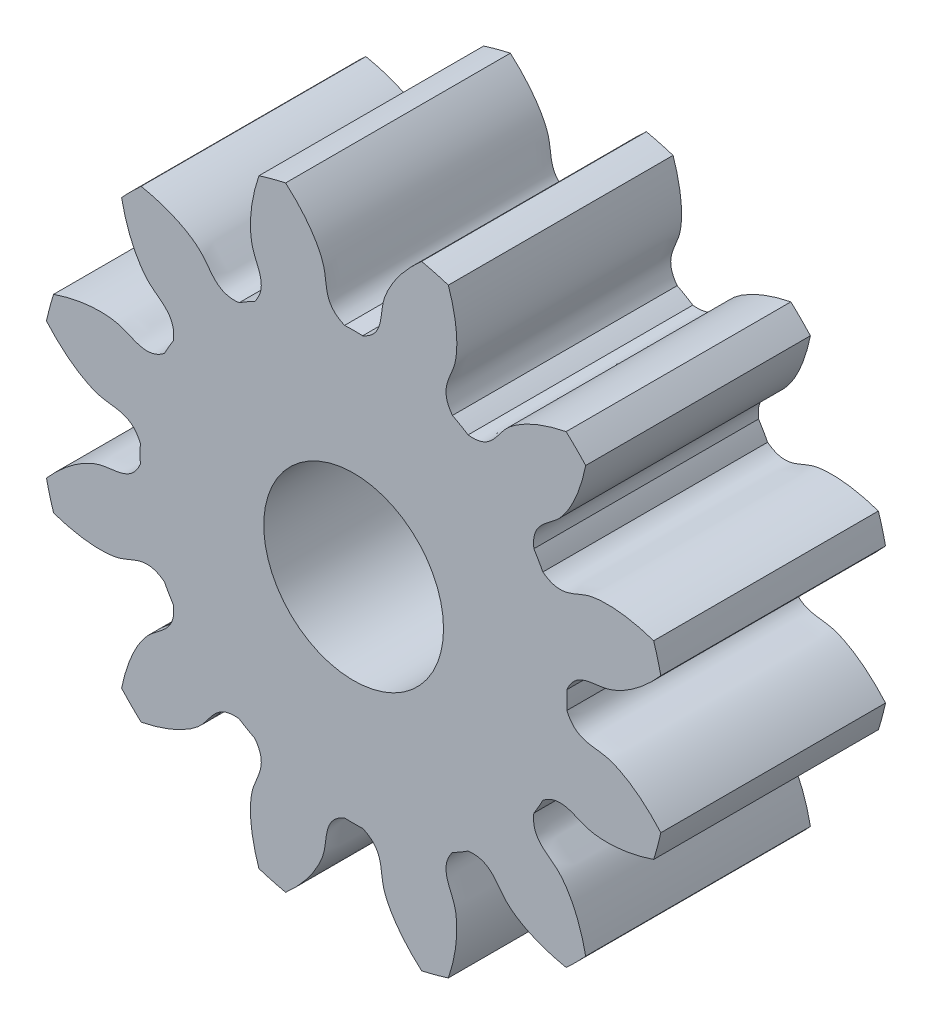
SolidWorks part; units mm, degrees
ref_plane "前视基准面" through (0, 0, 0) normal (0, 0, 1) x (1, 0, 0)
ref_plane "上视基准面" through (0, 0, 0) normal (0, 1, 0) x (1, 0, 0)
ref_plane "右视基准面" through (0, 0, 0) normal (1, 0, 0) x (0, 0, -1)
sketch "草图1" plane through (0, 0, 0) normal (0, 0, 1) x (1, 0, 0)
  arc A0 (2.4753, 14.2124) -> (1.8808, 14.0531) centre (3.988, 7.3778) ccw
  arc A1 (4.1888, 12.1235) -> (3.7871, 12.1235) centre (3.988, 7.3778) ccw
  arc A2 (6.0952, 14.0531) -> (5.5007, 14.2124) centre (3.988, 7.3778) ccw
  arc A3 (6.5348, 11.3873) -> (6.1869, 11.5881) centre (3.988, 7.3778) ccw
  arc A4 (9.1506, 12.1051) -> (8.7153, 12.5403) centre (3.988, 7.3778) ccw
  arc A5 (8.1983, 9.5767) -> (7.9975, 9.9246) centre (3.988, 7.3778) ccw
  arc A6 (10.8226, 8.8905) -> (10.6633, 9.485) centre (3.988, 7.3778) ccw
  arc A7 (8.7337, 7.1769) -> (8.7337, 7.5786) centre (3.988, 7.3778) ccw
  arc A8 (10.6633, 5.2705) -> (10.8226, 5.865) centre (3.988, 7.3778) ccw
  arc A9 (7.9975, 4.831) -> (8.1983, 5.1788) centre (3.988, 7.3778) ccw
  arc A10 (8.7153, 2.2152) -> (9.1506, 2.6504) centre (3.988, 7.3778) ccw
  arc A11 (6.1869, 3.1674) -> (6.5348, 3.3683) centre (3.988, 7.3778) ccw
  arc A12 (5.5007, 0.5432) -> (6.0952, 0.7025) centre (3.988, 7.3778) ccw
  arc A13 (3.7871, 2.632) -> (4.1888, 2.632) centre (3.988, 7.3778) ccw
  arc A14 (1.8808, 0.7025) -> (2.4753, 0.5432) centre (3.988, 7.3778) ccw
  arc A15 (1.4412, 3.3683) -> (1.789, 3.1674) centre (3.988, 7.3778) ccw
  arc A16 (-1.1746, 2.6504) -> (-0.7394, 2.2152) centre (3.988, 7.3778) ccw
  arc A17 (-0.2224, 5.1788) -> (-0.0215, 4.831) centre (3.988, 7.3778) ccw
  arc A18 (-2.8466, 5.865) -> (-2.6873, 5.2705) centre (3.988, 7.3778) ccw
  arc A19 (-0.7578, 7.5786) -> (-0.7578, 7.1769) centre (3.988, 7.3778) ccw
  arc A20 (-2.6873, 9.485) -> (-2.8466, 8.8905) centre (3.988, 7.3778) ccw
  arc A21 (-0.0215, 9.9246) -> (-0.2224, 9.5767) centre (3.988, 7.3778) ccw
  arc A22 (-0.7394, 12.5403) -> (-1.1746, 12.1051) centre (3.988, 7.3778) ccw
  arc A23 (1.789, 11.5881) -> (1.4412, 11.3873) centre (3.988, 7.3778) ccw
  circle A24 centre (3.988, 7.3778) radius 2
  spline S0 degree 3 poles (1.789, 11.5881) (2.1029, 12.0044) (1.813, 12.2937) (1.727, 12.6508) (1.7189, 12.6894) (1.71, 12.7428) (1.7021, 12.8055) (1.6959, 12.8774) (1.6921, 12.9585) (1.6916, 13.0487) (1.6949, 13.1479) (1.7029, 13.2559) (1.7162, 13.3724) (1.7391, 13.5207) (1.7769, 13.7033) (1.8272, 13.8894) (1.8652, 14.0073) (1.8808, 14.0531) knots 0 0 0 0 0.218015 0.222044 0.231522 0.242897 0.256167 0.271332 0.288394 0.307351 0.328204 0.350953 0.375597 0.402137 0.445502 0.493132 0.523596 0.523596 0.523596 0.523596
  spline S1 degree 3 poles (2.4753, 14.2124) (2.5311, 14.1635) (2.6222, 14.0794) (2.7418, 13.9578) (2.8358, 13.8543) (2.9197, 13.754) (2.9941, 13.6575) (3.0594, 13.5655) (3.116, 13.4786) (3.1645, 13.3972) (3.2054, 13.3219) (3.2393, 13.2531) (3.2668, 13.1912) (3.2884, 13.1367) (3.3028, 13.0959) (3.3118, 13.0673) (3.4136, 12.7226) (3.3072, 12.3271) (3.7871, 12.1235) knots 0.476404 0.476404 0.476404 0.476404 0.523219 0.554498 0.583882 0.61137 0.636962 0.660659 0.682459 0.702364 0.720374 0.736487 0.750705 0.763028 0.773454 0.777956 0.781985 1 1 1 1
  spline S2 degree 3 poles (4.1888, 12.1235) (4.6688, 12.3271) (4.5624, 12.7226) (4.6664, 13.0748) (4.6787, 13.1123) (4.6977, 13.163) (4.7222, 13.2213) (4.7528, 13.2866) (4.7901, 13.3588) (4.8347, 13.4372) (4.8872, 13.5214) (4.9481, 13.6109) (5.0179, 13.7052) (5.1118, 13.8221) (5.2359, 13.9614) (5.3725, 14.0974) (5.4643, 14.1806) (5.5007, 14.2124) knots 0 0 0 0 0.218015 0.222044 0.231522 0.242897 0.256167 0.271332 0.288394 0.307351 0.328204 0.350953 0.375597 0.402137 0.445502 0.493132 0.523596 0.523596 0.523596 0.523596
  spline S3 degree 3 poles (6.0952, 14.0531) (6.1192, 13.9828) (6.156, 13.8645) (6.1988, 13.6994) (6.2284, 13.5627) (6.251, 13.4338) (6.2672, 13.3131) (6.2777, 13.2008) (6.2833, 13.0972) (6.2846, 13.0025) (6.2823, 12.9168) (6.2773, 12.8403) (6.2701, 12.773) (6.2616, 12.7149) (6.2536, 12.6725) (6.2472, 12.6431) (6.163, 12.2937) (5.8731, 12.0044) (6.1869, 11.5881) knots 0.476404 0.476404 0.476404 0.476404 0.523219 0.554498 0.583882 0.61137 0.636962 0.660659 0.682459 0.702364 0.720374 0.736487 0.750705 0.763028 0.773454 0.777956 0.781985 1 1 1 1
  spline S4 degree 3 poles (6.5348, 11.3873) (7.0522, 11.3236) (7.1578, 11.7193) (7.424, 11.9724) (7.4535, 11.9987) (7.4952, 12.0331) (7.5455, 12.0713) (7.6047, 12.1126) (7.6731, 12.1564) (7.751, 12.202) (7.8385, 12.2487) (7.936, 12.2958) (8.0436, 12.3426) (8.1835, 12.3968) (8.3605, 12.4554) (8.5468, 12.5048) (8.6679, 12.531) (8.7153, 12.5403) knots 0 0 0 0 0.218015 0.222044 0.231522 0.242897 0.256167 0.271332 0.288394 0.307351 0.328204 0.350953 0.375597 0.402137 0.445502 0.493132 0.523596 0.523596 0.523596 0.523596
  spline S5 degree 3 poles (9.1506, 12.1051) (9.1362, 12.0323) (9.1089, 11.9114) (9.0634, 11.7471) (9.0207, 11.6139) (8.9758, 11.491) (8.9295, 11.3783) (8.8825, 11.2758) (8.8355, 11.1833) (8.7892, 11.1006) (8.7445, 11.0275) (8.7018, 10.9638) (8.662, 10.9091) (8.6256, 10.8631) (8.5974, 10.8303) (8.5771, 10.8081) (8.3295, 10.5476) (7.9338, 10.442) (7.9975, 9.9246) knots 0.476404 0.476404 0.476404 0.476404 0.523219 0.554498 0.583882 0.61137 0.636962 0.660659 0.682459 0.702364 0.720374 0.736487 0.750705 0.763028 0.773454 0.777956 0.781985 1 1 1 1
  spline S6 degree 3 poles (8.1983, 9.5767) (8.6146, 9.2628) (8.9039, 9.5528) (9.261, 9.6388) (9.2996, 9.6468) (9.353, 9.6558) (9.4157, 9.6637) (9.4876, 9.6699) (9.5687, 9.6736) (9.6589, 9.6742) (9.7581, 9.6709) (9.8661, 9.6629) (9.9827, 9.6496) (10.1309, 9.6267) (10.3135, 9.5888) (10.4996, 9.5385) (10.6175, 9.5006) (10.6633, 9.485) knots 0 0 0 0 0.218015 0.222044 0.231522 0.242897 0.256167 0.271332 0.288394 0.307351 0.328204 0.350953 0.375597 0.402137 0.445502 0.493132 0.523596 0.523596 0.523596 0.523596
  spline S7 degree 3 poles (10.8226, 8.8905) (10.7737, 8.8346) (10.6896, 8.7436) (10.5681, 8.624) (10.4645, 8.53) (10.3642, 8.446) (10.2677, 8.3716) (10.1758, 8.3063) (10.0888, 8.2497) (10.0074, 8.2012) (9.9321, 8.1603) (9.8633, 8.1264) (9.8014, 8.099) (9.7469, 8.0774) (9.7061, 8.063) (9.6775, 8.0539) (9.3328, 7.9521) (8.9373, 8.0586) (8.7337, 7.5786) knots 0.476404 0.476404 0.476404 0.476404 0.523219 0.554498 0.583882 0.61137 0.636962 0.660659 0.682459 0.702364 0.720374 0.736487 0.750705 0.763028 0.773454 0.777956 0.781985 1 1 1 1
  spline S8 degree 3 poles (8.7337, 7.1769) (8.9373, 6.697) (9.3328, 6.8034) (9.685, 6.6994) (9.7225, 6.687) (9.7732, 6.6681) (9.8315, 6.6436) (9.8968, 6.613) (9.969, 6.5757) (10.0474, 6.5311) (10.1316, 6.4786) (10.2212, 6.4177) (10.3154, 6.3479) (10.4324, 6.2539) (10.5716, 6.1298) (10.7076, 5.9932) (10.7908, 5.9014) (10.8226, 5.865) knots 0 0 0 0 0.218015 0.222044 0.231522 0.242897 0.256167 0.271332 0.288394 0.307351 0.328204 0.350953 0.375597 0.402137 0.445502 0.493132 0.523596 0.523596 0.523596 0.523596
  spline S9 degree 3 poles (10.6633, 5.2705) (10.593, 5.2466) (10.4747, 5.2097) (10.3096, 5.167) (10.1729, 5.1374) (10.0441, 5.1148) (9.9233, 5.0986) (9.811, 5.088) (9.7074, 5.0825) (9.6127, 5.0812) (9.527, 5.0834) (9.4505, 5.0885) (9.3832, 5.0956) (9.3252, 5.1042) (9.2827, 5.1121) (9.2533, 5.1186) (8.9039, 5.2028) (8.6146, 5.4927) (8.1983, 5.1788) knots 0.476404 0.476404 0.476404 0.476404 0.523219 0.554498 0.583882 0.61137 0.636962 0.660659 0.682459 0.702364 0.720374 0.736487 0.750705 0.763028 0.773454 0.777956 0.781985 1 1 1 1
  spline S10 degree 3 poles (7.9975, 4.831) (7.9338, 4.3135) (8.3295, 4.2079) (8.5826, 3.9417) (8.6089, 3.9123) (8.6433, 3.8705) (8.6815, 3.8202) (8.7228, 3.761) (8.7666, 3.6927) (8.8122, 3.6148) (8.8589, 3.5272) (8.906, 3.4297) (8.9528, 3.3222) (9.007, 3.1823) (9.0656, 3.0052) (9.1151, 2.8189) (9.1412, 2.6978) (9.1506, 2.6504) knots 0 0 0 0 0.218015 0.222044 0.231522 0.242897 0.256167 0.271332 0.288394 0.307351 0.328204 0.350953 0.375597 0.402137 0.445502 0.493132 0.523596 0.523596 0.523596 0.523596
  spline S11 degree 3 poles (8.7153, 2.2152) (8.6425, 2.2296) (8.5216, 2.2569) (8.3573, 2.3024) (8.2241, 2.3451) (8.1012, 2.3899) (7.9886, 2.4363) (7.886, 2.4833) (7.7935, 2.5303) (7.7108, 2.5765) (7.6377, 2.6213) (7.574, 2.664) (7.5193, 2.7038) (7.4733, 2.7402) (7.4405, 2.7683) (7.4183, 2.7886) (7.1578, 3.0362) (7.0522, 3.4319) (6.5348, 3.3683) knots 0.476404 0.476404 0.476404 0.476404 0.523219 0.554498 0.583882 0.61137 0.636962 0.660659 0.682459 0.702364 0.720374 0.736487 0.750705 0.763028 0.773454 0.777956 0.781985 1 1 1 1
  spline S12 degree 3 poles (6.1869, 3.1674) (5.8731, 2.7512) (6.163, 2.4618) (6.249, 2.1048) (6.2571, 2.0661) (6.266, 2.0127) (6.2739, 1.9501) (6.2801, 1.8782) (6.2838, 1.7971) (6.2844, 1.7068) (6.2811, 1.6076) (6.2731, 1.4996) (6.2598, 1.3831) (6.2369, 1.2349) (6.1991, 1.0522) (6.1487, 0.8662) (6.1108, 0.7482) (6.0952, 0.7025) knots 0 0 0 0 0.218015 0.222044 0.231522 0.242897 0.256167 0.271332 0.288394 0.307351 0.328204 0.350953 0.375597 0.402137 0.445502 0.493132 0.523596 0.523596 0.523596 0.523596
  spline S13 degree 3 poles (5.5007, 0.5432) (5.4448, 0.5921) (5.3538, 0.6761) (5.2342, 0.7977) (5.1402, 0.9013) (5.0562, 1.0016) (4.9818, 1.098) (4.9166, 1.19) (4.8599, 1.277) (4.8114, 1.3583) (4.7705, 1.4337) (4.7367, 1.5025) (4.7092, 1.5643) (4.6876, 1.6188) (4.6732, 1.6596) (4.6641, 1.6883) (4.5624, 2.033) (4.6688, 2.4285) (4.1888, 2.632) knots 0.476404 0.476404 0.476404 0.476404 0.523219 0.554498 0.583882 0.61137 0.636962 0.660659 0.682459 0.702364 0.720374 0.736487 0.750705 0.763028 0.773454 0.777956 0.781985 1 1 1 1
  spline S14 degree 3 poles (3.7871, 2.632) (3.3072, 2.4285) (3.4136, 2.033) (3.3096, 1.6807) (3.2972, 1.6432) (3.2783, 1.5925) (3.2538, 1.5343) (3.2232, 1.4689) (3.1859, 1.3968) (3.1413, 1.3184) (3.0888, 1.2341) (3.0279, 1.1446) (2.9581, 1.0503) (2.8641, 0.9334) (2.7401, 0.7942) (2.6034, 0.6582) (2.5116, 0.575) (2.4753, 0.5432) knots 0 0 0 0 0.218015 0.222044 0.231522 0.242897 0.256167 0.271332 0.288394 0.307351 0.328204 0.350953 0.375597 0.402137 0.445502 0.493132 0.523596 0.523596 0.523596 0.523596
  spline S15 degree 3 poles (1.8808, 0.7025) (1.8568, 0.7728) (1.82, 0.8911) (1.7772, 1.0562) (1.7476, 1.1928) (1.725, 1.3217) (1.7088, 1.4424) (1.6983, 1.5547) (1.6927, 1.6583) (1.6914, 1.7531) (1.6936, 1.8388) (1.6987, 1.9153) (1.7059, 1.9826) (1.7144, 2.0406) (1.7223, 2.0831) (1.7288, 2.1125) (1.813, 2.4618) (2.1029, 2.7512) (1.789, 3.1674) knots 0.476404 0.476404 0.476404 0.476404 0.523219 0.554498 0.583882 0.61137 0.636962 0.660659 0.682459 0.702364 0.720374 0.736487 0.750705 0.763028 0.773454 0.777956 0.781985 1 1 1 1
  spline S16 degree 3 poles (1.4412, 3.3683) (0.9238, 3.4319) (0.8182, 3.0362) (0.552, 2.7832) (0.5225, 2.7569) (0.4807, 2.7225) (0.4304, 2.6843) (0.3712, 2.6429) (0.3029, 2.5991) (0.225, 2.5535) (0.1374, 2.5068) (0.0399, 2.4597) (-0.0676, 2.413) (-0.2075, 2.3587) (-0.3846, 2.3002) (-0.5709, 2.2507) (-0.692, 2.2246) (-0.7394, 2.2152) knots 0 0 0 0 0.218015 0.222044 0.231522 0.242897 0.256167 0.271332 0.288394 0.307351 0.328204 0.350953 0.375597 0.402137 0.445502 0.493132 0.523596 0.523596 0.523596 0.523596
  spline S17 degree 3 poles (-1.1746, 2.6504) (-1.1602, 2.7233) (-1.1329, 2.8442) (-1.0874, 3.0085) (-1.0447, 3.1417) (-0.9998, 3.2646) (-0.9535, 3.3772) (-0.9065, 3.4797) (-0.8595, 3.5722) (-0.8133, 3.6549) (-0.7685, 3.728) (-0.7258, 3.7918) (-0.686, 3.8465) (-0.6496, 3.8925) (-0.6215, 3.9253) (-0.6012, 3.9475) (-0.3536, 4.2079) (0.0422, 4.3135) (-0.0215, 4.831) knots 0.476404 0.476404 0.476404 0.476404 0.523219 0.554498 0.583882 0.61137 0.636962 0.660659 0.682459 0.702364 0.720374 0.736487 0.750705 0.763028 0.773454 0.777956 0.781985 1 1 1 1
  spline S18 degree 3 poles (-0.2224, 5.1788) (-0.6386, 5.4927) (-0.9279, 5.2028) (-1.285, 5.1167) (-1.3236, 5.1087) (-1.377, 5.0998) (-1.4397, 5.0919) (-1.5116, 5.0857) (-1.5927, 5.0819) (-1.683, 5.0813) (-1.7822, 5.0847) (-1.8901, 5.0927) (-2.0067, 5.1059) (-2.1549, 5.1289) (-2.3376, 5.1667) (-2.5236, 5.217) (-2.6416, 5.2549) (-2.6873, 5.2705) knots 0 0 0 0 0.218015 0.222044 0.231522 0.242897 0.256167 0.271332 0.288394 0.307351 0.328204 0.350953 0.375597 0.402137 0.445502 0.493132 0.523596 0.523596 0.523596 0.523596
  spline S19 degree 3 poles (-2.8466, 5.865) (-2.7977, 5.9209) (-2.7137, 6.012) (-2.5921, 6.1316) (-2.4885, 6.2255) (-2.3882, 6.3095) (-2.2918, 6.3839) (-2.1998, 6.4492) (-2.1128, 6.5058) (-2.0314, 6.5543) (-1.9561, 6.5952) (-1.8873, 6.6291) (-1.8255, 6.6566) (-1.7709, 6.6782) (-1.7302, 6.6925) (-1.7015, 6.7016) (-1.3568, 6.8034) (-0.9613, 6.697) (-0.7578, 7.1769) knots 0.476404 0.476404 0.476404 0.476404 0.523219 0.554498 0.583882 0.61137 0.636962 0.660659 0.682459 0.702364 0.720374 0.736487 0.750705 0.763028 0.773454 0.777956 0.781985 1 1 1 1
  spline S20 degree 3 poles (-0.7578, 7.5786) (-0.9613, 8.0586) (-1.3568, 7.9521) (-1.7091, 8.0562) (-1.7466, 8.0685) (-1.7973, 8.0875) (-1.8555, 8.112) (-1.9209, 8.1425) (-1.993, 8.1799) (-2.0714, 8.2245) (-2.1556, 8.277) (-2.2452, 8.3379) (-2.3395, 8.4076) (-2.4564, 8.5016) (-2.5956, 8.6257) (-2.7316, 8.7623) (-2.8148, 8.8541) (-2.8466, 8.8905) knots 0 0 0 0 0.218015 0.222044 0.231522 0.242897 0.256167 0.271332 0.288394 0.307351 0.328204 0.350953 0.375597 0.402137 0.445502 0.493132 0.523596 0.523596 0.523596 0.523596
  spline S21 degree 3 poles (-2.6873, 9.485) (-2.617, 9.509) (-2.4987, 9.5458) (-2.3336, 9.5885) (-2.1969, 9.6182) (-2.0681, 9.6407) (-1.9474, 9.657) (-1.8351, 9.6675) (-1.7315, 9.6731) (-1.6367, 9.6744) (-1.551, 9.6721) (-1.4745, 9.6671) (-1.4072, 9.6599) (-1.3492, 9.6514) (-1.3067, 9.6434) (-1.2773, 9.6369) (-0.9279, 9.5528) (-0.6386, 9.2628) (-0.2224, 9.5767) knots 0.476404 0.476404 0.476404 0.476404 0.523219 0.554498 0.583882 0.61137 0.636962 0.660659 0.682459 0.702364 0.720374 0.736487 0.750705 0.763028 0.773454 0.777956 0.781985 1 1 1 1
  spline S22 degree 3 poles (-0.0215, 9.9246) (0.0422, 10.442) (-0.3536, 10.5476) (-0.6066, 10.8138) (-0.6329, 10.8432) (-0.6673, 10.885) (-0.7055, 10.9353) (-0.7468, 10.9945) (-0.7907, 11.0629) (-0.8363, 11.1407) (-0.883, 11.2283) (-0.9301, 11.3258) (-0.9768, 11.4334) (-1.0311, 11.5732) (-1.0896, 11.7503) (-1.1391, 11.9366) (-1.1652, 12.0577) (-1.1746, 12.1051) knots 0 0 0 0 0.218015 0.222044 0.231522 0.242897 0.256167 0.271332 0.288394 0.307351 0.328204 0.350953 0.375597 0.402137 0.445502 0.493132 0.523596 0.523596 0.523596 0.523596
  spline S23 degree 3 poles (-0.7394, 12.5403) (-0.6665, 12.5259) (-0.5456, 12.4987) (-0.3813, 12.4532) (-0.2481, 12.4105) (-0.1252, 12.3656) (-0.0126, 12.3193) (0.0899, 12.2723) (0.1825, 12.2253) (0.2651, 12.179) (0.3382, 12.1342) (0.402, 12.0916) (0.4567, 12.0518) (0.5027, 12.0154) (0.5355, 11.9872) (0.5577, 11.9669) (0.8182, 11.7193) (0.9238, 11.3236) (1.4412, 11.3873) knots 0.476404 0.476404 0.476404 0.476404 0.523219 0.554498 0.583882 0.61137 0.636962 0.660659 0.682459 0.702364 0.720374 0.736487 0.750705 0.763028 0.773454 0.777956 0.781985 1 1 1 1
extrude "凸台-拉伸1" add sketch "草图1" along normal blind 5
